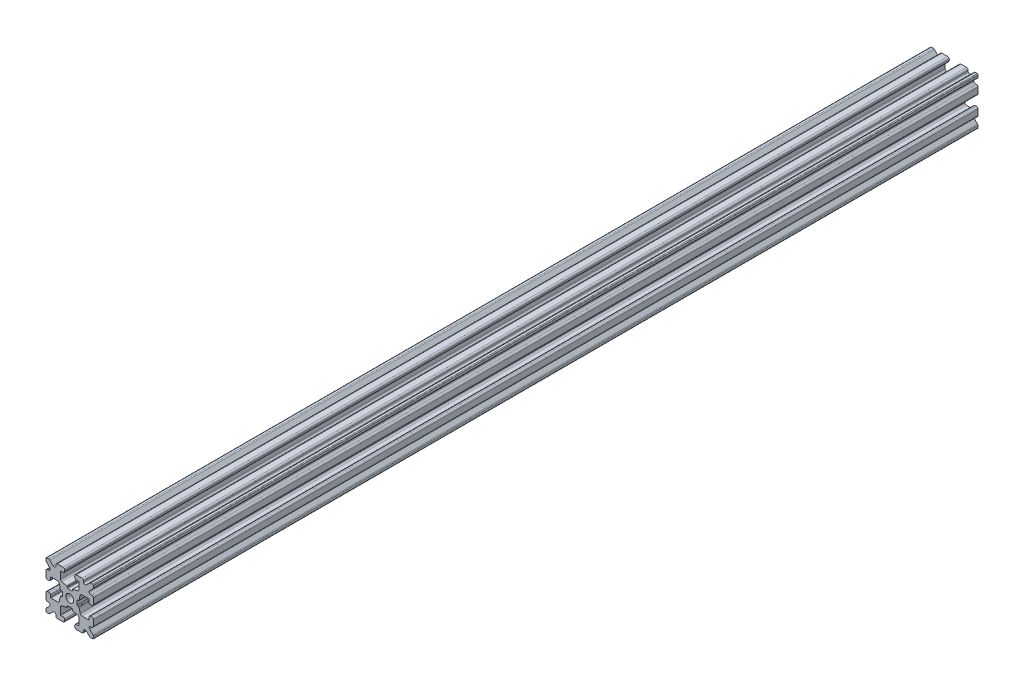
SolidWorks part; units mm, degrees
ref_plane "Front Plane" through (0, 0, 0) normal (0, 0, 1) x (1, 0, 0)
ref_plane "Top Plane" through (0, 0, 0) normal (0, 1, 0) x (1, 0, 0)
ref_plane "Right Plane" through (0, 0, 0) normal (1, 0, 0) x (0, 0, -1)
sketch "Sketch1" plane through (0, 0, 0) normal (0, 0, 1) x (1, 0, 0)
  line L1 (-7.5, -7.5) -> (7.5, -7.5)
  line L2 (-7.5, -7.5) -> (-7.5, 7.5)
  line L3 (-7.5, 7.5) -> (7.5, 7.5)
  line L4 (7.5, -7.5) -> (7.5, 7.5)
  line L5 (-7.5, -7.5) -> (7.5, 7.5) construction
  line L6 (-7.5, 7.5) -> (7.5, -7.5) construction
  circle A0 centre (0, 0) radius 1.25
  point P0 (0, 0)
  dimension "D2" = 2.5
  dimension "D1" = 15
extrude "Boss-Extrude1" add sketch "Sketch1" along normal mid plane 280
fillet "Fillet1" radius 0.25 4 edges at (7.5, -7.5, 0) (-7.5, -7.5, 0) (7.5, 7.5, 0) (-7.5, 7.5, 0)
sketch "Sketch2" plane through (0, 0, 140) normal (0, 0, 1) x (1, 0, 0)
  line L0 (-7.5, 7.25) -> (-7.5, -7.25) construction
  line L1 (-7.5, 1.6) -> (-6.1, 1.6)
  line L2 (-7.5, 1.6) -> (-7.5, -1.6)
  line L3 (-7.5, -1.6) -> (-6.1, -1.6)
  line L4 (-6.1, 1.6) -> (-6.1, 2.9)
  line L5 (0, 0) -> (-12.1036, 0) construction
  line L6 (-6.1, -2.9) -> (-3.4, -2.9)
  line L7 (0, 0) -> (-7.25, 7.25) construction
  line L8 (-6.1, 2.9) -> (-3.4, 2.9)
  line L9 (-3.4, -2.9) -> (-3.4, 2.9)
  line L10 (55, 0) -> (-55, 0) construction
  line L11 (-6.1, -2.9) -> (-6.1, -1.6)
  line L12 (2.9, 6.1) -> (1.6, 6.1)
  line L13 (2.9, 3.4) -> (-2.9, 3.4)
  line L14 (-2.9, 6.1) -> (-2.9, 3.4)
  line L15 (2.9, 6.1) -> (2.9, 3.4)
  line L16 (-1.6, 6.1) -> (-2.9, 6.1)
  line L17 (1.6, 7.5) -> (1.6, 6.1)
  line L18 (-1.6, 7.5) -> (1.6, 7.5)
  line L19 (-1.6, 7.5) -> (-1.6, 6.1)
  line L20 (-1.6, -7.5) -> (-1.6, -6.1)
  line L21 (-1.6, -7.5) -> (1.6, -7.5)
  line L22 (1.6, -7.5) -> (1.6, -6.1)
  line L23 (-1.6, -6.1) -> (-2.9, -6.1)
  line L24 (2.9, -6.1) -> (2.9, -3.4)
  line L25 (-2.9, -6.1) -> (-2.9, -3.4)
  line L26 (2.9, -3.4) -> (-2.9, -3.4)
  line L27 (2.9, -6.1) -> (1.6, -6.1)
  line L28 (6.1, -2.9) -> (6.1, -1.6)
  line L29 (3.4, -2.9) -> (3.4, 2.9)
  line L30 (6.1, 2.9) -> (3.4, 2.9)
  line L31 (6.1, -2.9) -> (3.4, -2.9)
  line L32 (6.1, 1.6) -> (6.1, 2.9)
  line L33 (7.5, -1.6) -> (6.1, -1.6)
  line L34 (7.5, 1.6) -> (7.5, -1.6)
  line L35 (7.5, 1.6) -> (6.1, 1.6)
  dimension "D1" = 3.2
  dimension "D2" = 5.8
  dimension "D3" = 1.4
  dimension "D4" = 2.7
extrude "Cut-Extrude1" cut sketch "Sketch2" against normal through all
sketch "Sketch4" plane through (0, 0, 140) normal (0, 0, 1) x (1, 0, 0)
  line L0 (-3.4, 2.9) -> (-2.75, 0)
  line L1 (55, 0) -> (-55, 0) construction
  line L2 (-2.75, 0) -> (-3.4, -2.9)
  line L3 (-3.4, -2.9) -> (-3.4, 2.9) construction
  line L4 (-3.4, 2.9) -> (-3.4, -2.9)
  line L5 (-2.9, 3.4) -> (0, 2.75)
  line L6 (0, 2.75) -> (2.9, 3.4)
  line L7 (2.9, 3.4) -> (-2.9, 3.4)
  line L8 (3.4, 2.9) -> (2.75, 0)
  line L9 (2.75, 0) -> (3.4, -2.9)
  line L10 (3.4, -2.9) -> (3.4, 2.9)
  line L11 (-2.9, -3.4) -> (0, -2.75)
  line L12 (0, -2.75) -> (2.9, -3.4)
  line L13 (2.9, -3.4) -> (-2.9, -3.4)
  circle A2 centre (0, 0) radius 2.75
  circle A3 centre (0, 0) radius 2.75 construction
  dimension "D1" = 1.5
extrude "Cut-Extrude3" cut sketch "Sketch4" against normal through all
fillet "Fillet3" radius 0.5 16 edges at (-6.1, -1.6, 0) (-7.5, -1.6, 0) (-6.1, 1.6, 0) (-7.5, 1.6, 0) (-1.6, -7.5, 0) (-1.6, -6.1, 0) (1.6, -7.5, 0) (1.6, -6.1, 0) (6.1, -1.6, 0) (7.5, -1.6, 0) (7.5, 1.6, 0) (6.1, 1.6, 0) (1.6, 7.5, 0) (1.6, 6.1, 0) (-1.6, 7.5, 0) (-1.6, 6.1, 0)
fillet "Fillet4" radius 0.5 8 edges at (-3.4, 2.9, 0) (-3.4, -2.9, 0) (2.9, -3.4, 0) (-2.9, -3.4, 0) (3.4, -2.9, 0) (3.4, 2.9, 0) (-2.9, 3.4, 0) (2.9, 3.4, 0)
fillet "Fillet5" radius 3 4 edges at (0, -2.75, 0) (2.75, 0, 0) (-2.75, 0, 0) (0, 2.75, 0)
fillet "Fillet6" radius 0.2 8 edges at (-2.9, -6.1, 0) (2.9, -6.1, 0) (6.1, -2.9, 0) (6.1, 2.9, 0) (2.9, 6.1, 0) (-2.9, 6.1, 0) (-6.1, -2.9, 0) (-6.1, 2.9, 0)
sketch "Sketch5" plane through (0, 0, 140) normal (0, 0, 1) x (1, 0, 0)
  line L0 (0, 0) -> (-7.25, 7.25) construction
  line L1 (-7.5, 6.4393) -> (-5.4607, 4.4)
  line L2 (-6.4393, 7.5) -> (-4.4, 5.4607)
  line L3 (-7.5, 4.4) -> (-5.4607, 4.4)
  line L4 (-3.8003, 2.9) -> (-5.9, 2.9) construction
  line L5 (0, 0) -> (-12.1819, 0) construction
  line L6 (-4.4, 7.5) -> (-4.4, 5.4607)
  line L7 (-2.9, 5.9) -> (-2.9, 3.8003) construction
  line L8 (-7.5, 6.4393) -> (-7.5, 4.4)
  line L9 (-7.5, 7.25) -> (-7.5, 2.1) construction
  line L10 (2.1, -7.5) -> (7.25, -7.5) construction
  line L11 (7.5, -7.25) -> (7.5, -2.1) construction
  line L12 (7.25, 7.5) -> (2.1, 7.5) construction
  line L13 (-2.1, 7.5) -> (-7.25, 7.5) construction
  line L14 (-4.4, 7.5) -> (-6.4393, 7.5)
  line L16 (55, 0) -> (-55, 0) construction
  line L17 (0, 0) -> (0, 10.993) construction
  line L18 (0, -54.6431) -> (0, 54.6431) construction
  line L20 (4.4, 7.5) -> (6.4393, 7.5)
  line L22 (7.5, 6.4393) -> (7.5, 4.4)
  line L23 (4.4, 7.5) -> (4.4, 5.4607)
  line L24 (7.5, 4.4) -> (5.4607, 4.4)
  line L25 (6.4393, 7.5) -> (4.4, 5.4607)
  line L26 (7.5, 6.4393) -> (5.4607, 4.4)
  line L27 (7.5, -6.4393) -> (5.4607, -4.4)
  line L28 (6.4393, -7.5) -> (4.4, -5.4607)
  line L29 (7.5, -4.4) -> (5.4607, -4.4)
  line L30 (4.4, -7.5) -> (4.4, -5.4607)
  line L31 (7.5, -6.4393) -> (7.5, -4.4)
  line L33 (4.4, -7.5) -> (6.4393, -7.5)
  line L36 (-4.4, -7.5) -> (-6.4393, -7.5)
  line L38 (-7.5, -6.4393) -> (-7.5, -4.4)
  line L39 (-4.4, -7.5) -> (-4.4, -5.4607)
  line L40 (-7.5, -4.4) -> (-5.4607, -4.4)
  line L41 (-6.4393, -7.5) -> (-4.4, -5.4607)
  line L42 (-7.5, -6.4393) -> (-5.4607, -4.4)
  dimension "D1" = 1.5
  dimension "D2" = 1.5
  dimension "D3" = 1.5
extrude "Cut-Extrude4" cut sketch "Sketch5" against normal through all
fillet "Fillet8" radius 0.5 24 edges at (-5.4607, 4.4, 0) (-7.5, 4.4, 0) (-5.4607, -4.4, 0) (-7.5, -4.4, 0) (-4.4, -7.5, 0) (-4.4, -5.4607, 0) (4.4, -7.5, 0) (4.4, -5.4607, 0) (5.4607, -4.4, 0) (7.5, -4.4, 0) (7.5, 4.4, 0) (5.4607, 4.4, 0) (4.4, 5.4607, 0) (4.4, 7.5, 0) (-4.4, 5.4607, 0) (-4.4, 7.5, 0) (-6.4393, 7.5, 0) (-7.5, 6.4393, 0) (6.4393, 7.5, 0) (7.5, 6.4393, 0) (6.4393, -7.5, 0) (7.5, -6.4393, 0) (-6.4393, -7.5, 0) (-7.5, -6.4393, 0)
sketch "Sketch6" plane through (0, 0, 140) normal (0, 0, 1) x (1, 0, 0)
  line L0 (0, 0) -> (0, 11.013) construction
  line L1 (0.6561, 2.8971) -> (2.1235, 2.8971) construction
  line L2 (0, -54.6431) -> (0, 54.6431) construction
  line L3 (0, 0) -> (7.25, 7.25) construction
  line L4 (7.5, 0.8255) -> (7.5, -0.8255)
  line L5 (2.3471, 0.8255) -> (7.5, 0.8255)
  line L6 (0, 0) -> (12.4016, 0) construction
  line L7 (0.8255, -7.5) -> (-0.8255, -7.5)
  line L8 (2.3471, -0.8255) -> (2.3471, 0.8255)
  line L9 (0.8255, -2.3471) -> (0.8255, -7.5)
  line L10 (7.5, -0.8255) -> (2.3471, -0.8255)
  line L11 (-7.5, -0.8255) -> (-2.3471, -0.8255)
  line L12 (-2.3471, -0.8255) -> (-2.3471, 0.8255)
  line L13 (-0.8255, -2.3471) -> (0.8255, -2.3471)
  line L14 (-0.8255, 7.5) -> (-0.8255, 2.3471)
  line L15 (-0.8255, 2.3471) -> (0.8255, 2.3471)
  line L16 (-0.8255, -7.5) -> (-0.8255, -2.3471)
  line L17 (0.8255, 2.3471) -> (0.8255, 7.5)
  line L18 (0.8255, 7.5) -> (-0.8255, 7.5)
  line L19 (3.9, 7.5) -> (2.1, 7.5) construction
  line L20 (-2.3471, 0.8255) -> (-7.5, 0.8255)
  line L21 (-7.5, 0.8255) -> (-7.5, -0.8255)
  point P5 (0, -2.5973)
  point P7 (0, 2.5973)
  dimension "D3" = 0.55
  dimension "D1" = 1.651
extrude "Cut-Extrude5" cut sketch "Sketch6" against normal through all
fillet "Fillet10" radius 0.2 16 edges at (-2.935, 0.8255, 0) (-2.935, -0.8255, 0) (2.935, -0.8255, 0) (2.935, 0.8255, 0) (0.8255, 2.935, 0) (-0.8255, 2.935, 0) (-2.3471, 0.8255, 0) (-2.3471, -0.8255, 0) (0.8255, 2.3471, 0) (-0.8255, 2.3471, 0) (2.3471, 0.8255, 0) (2.3471, -0.8255, 0) (0.8255, -2.935, 0) (0.8255, -2.3471, 0) (-0.8255, -2.3471, 0) (-0.8255, -2.935, 0)
